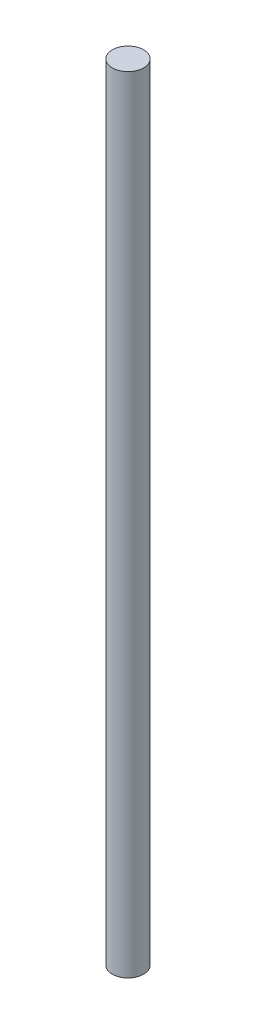
SolidWorks part; units mm, degrees
ref_plane "Front Plane" through (0, 0, 0) normal (0, 0, 1) x (1, 0, 0)
ref_plane "Top Plane" through (0, 0, 0) normal (0, 1, 0) x (1, 0, 0)
ref_plane "Right Plane" through (0, 0, 0) normal (1, 0, 0) x (0, 0, -1)
sketch "Sketch2" plane through (0, 0, 0) normal (0, 1, 0) x (1, 0, 0)
  circle A0 centre (0, 0) radius 3
  dimension "D1" = 6
extrude "Boss-Extrude1" add sketch "Sketch2" along normal blind 150
